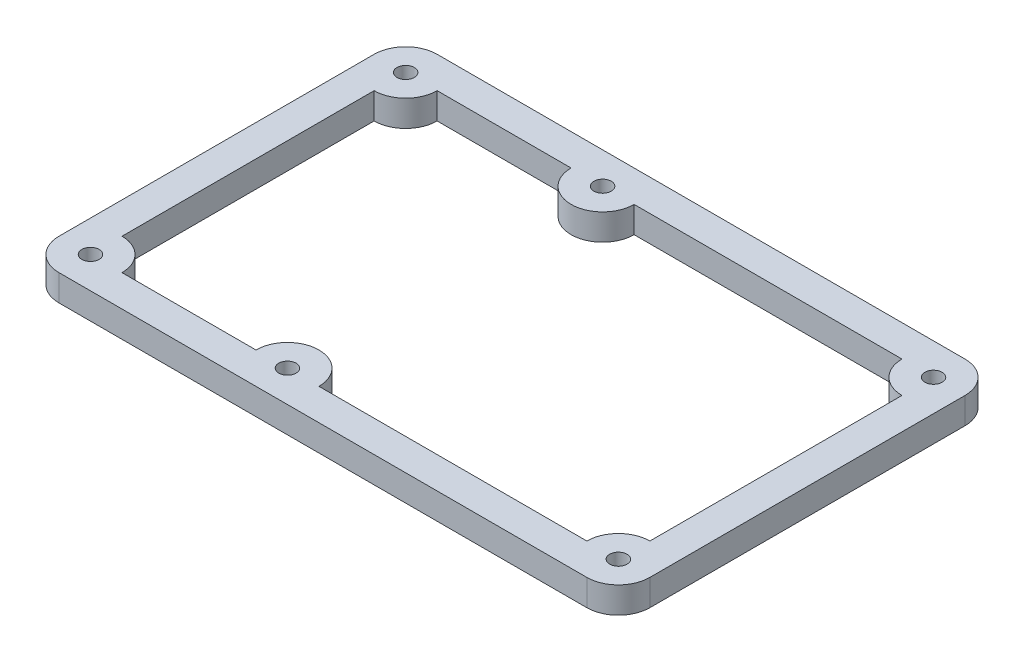
SolidWorks part; units mm, degrees
ref_plane "前视" through (0, 0, 0) normal (0, 0, 1) x (1, 0, 0)
ref_plane "上视" through (0, 0, 0) normal (0, 1, 0) x (1, 0, 0)
ref_plane "右视" through (0, 0, 0) normal (1, 0, 0) x (0, 0, -1)
sketch "草图1" plane through (0, 0, 0) normal (0, 1, 0) x (1, 0, 0)
  line L1 (-50.7858, -6.8634) -> (-25.2858, -6.8634)
  line L2 (-56.7858, -0.8634) -> (-56.7858, 47.1366)
  line L3 (-50.7858, 53.1366) -> (-25.2858, 53.1366)
  line L6 (37.7142, -6.8634) -> (-13.2858, -6.8634)
  line L7 (-62.7858, 53.1366) -> (-62.7858, -6.8634)
  line L8 (-56.7858, 59.1366) -> (43.7142, 59.1366)
  line L9 (49.7142, 53.1366) -> (49.7142, -6.8634)
  line L10 (-56.7858, -12.8634) -> (43.7142, -12.8634)
  line L12 (-13.2858, 53.1366) -> (37.7142, 53.1366)
  line L13 (43.7142, 47.1366) -> (43.7142, -0.8634)
  circle A0 centre (-56.7858, 53.1366) radius 1.65
  circle A1 centre (-19.2858, 53.1366) radius 1.65
  circle A2 centre (43.7142, 53.1366) radius 1.65
  circle A3 centre (-56.7858, -6.8634) radius 1.65
  circle A4 centre (-19.2858, -6.8634) radius 1.65
  circle A5 centre (43.7142, -6.8634) radius 1.65
  arc A6 (-56.7858, 59.1366) -> (-62.7858, 53.1366) centre (-56.7858, 53.1366) ccw
  arc A7 (37.7142, 53.1366) -> (43.7142, 47.1366) centre (43.7142, 53.1366) ccw
  arc A8 (-50.7858, -6.8634) -> (-56.7858, -0.8634) centre (-56.7858, -6.8634) ccw
  arc A9 (43.7142, -0.8634) -> (37.7142, -6.8634) centre (43.7142, -6.8634) ccw
  arc A10 (-25.2858, 53.1366) -> (-13.2858, 53.1366) centre (-19.2858, 53.1366) ccw
  arc A11 (-13.2858, -6.8634) -> (-25.2858, -6.8634) centre (-19.2858, -6.8634) ccw
  arc A12 (49.7142, 53.1366) -> (43.7142, 59.1366) centre (43.7142, 53.1366) ccw
  arc A13 (-56.7858, 47.1366) -> (-50.7858, 53.1366) centre (-56.7858, 53.1366) ccw
  arc A14 (43.7142, -12.8634) -> (49.7142, -6.8634) centre (43.7142, -6.8634) ccw
  arc A15 (-62.7858, -6.8634) -> (-56.7858, -12.8634) centre (-56.7858, -6.8634) ccw
extrude "凸台-拉伸1" add sketch "草图1" along normal blind 5
